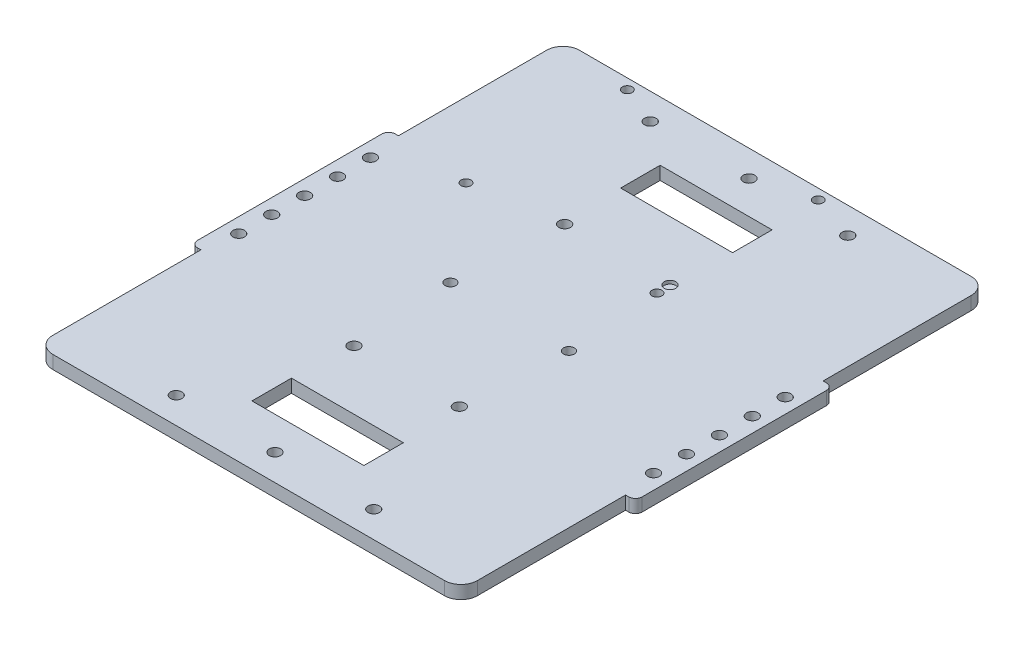
SolidWorks part; units mm, degrees
ref_plane "前视基准面" through (0, 0, 0) normal (0, 0, 1) x (1, 0, 0)
ref_plane "上视基准面" through (0, 0, 0) normal (0, 1, 0) x (1, 0, 0)
ref_plane "右视基准面" through (0, 0, 0) normal (1, 0, 0) x (0, 0, -1)
sketch "草图1" plane through (0, 0, 0) normal (0, 1, 0) x (1, 0, 0)
  line L1 (-67.5, 50) -> (67.5, 50)
  line L2 (-67.5, 50) -> (-67.5, -50)
  line L3 (-67.5, -50) -> (67.5, -50)
  line L4 (67.5, 50) -> (67.5, -50)
  line L5 (-67.5, 50) -> (67.5, -50) construction
  line L6 (-67.5, -50) -> (67.5, 50) construction
  point P0 (0, 0)
  dimension "D1" = 100
  dimension "D2" = 135
extrude "凸台-拉伸1" add sketch "草图1" along normal blind 4
sketch "草图2" plane through (0, 0, 50) normal (0, 0, 1) x (1, 0, 0)
  line L4 (-67.5, 0) -> (67.5, 0)
  line L5 (67.5, 0) -> (67.5, 4)
  line L6 (67.5, 4) -> (-67.5, 4)
  line L7 (-67.5, 4) -> (-67.5, 0)
  line L8 (-67.5, 0) -> (67.5, 0)
  line L9 (67.5, 0) -> (67.5, 4)
  line L10 (67.5, 4) -> (-67.5, 4)
  line L11 (-67.5, 4) -> (-67.5, 0)
  dimension "D1" = 0
extrude "凸台-拉伸2" add sketch "草图2" along normal blind 60
sketch "草图3" plane through (0, 4, 0) normal (0, 1, 0) x (1, 0, 0)
  line L1 (-67.5, 50) -> (-64.5, 50)
  line L2 (-67.5, 50) -> (-67.5, 0)
  line L3 (-67.5, 0) -> (-64.5, 0)
  line L4 (-64.5, 50) -> (-64.5, 0)
  line L5 (67.5, 50) -> (64.5, 50)
  line L6 (67.5, 50) -> (67.5, 0)
  line L7 (67.5, 0) -> (64.5, 0)
  line L8 (64.5, 50) -> (64.5, 0)
  line L9 (-67.5, -110) -> (-64.5, -110)
  line L10 (-67.5, -110) -> (-67.5, -60)
  line L11 (-67.5, -60) -> (-64.5, -60)
  line L12 (-64.5, -110) -> (-64.5, -60)
  line L13 (67.5, -110) -> (64.5, -110)
  line L14 (67.5, -110) -> (67.5, -60)
  line L15 (67.5, -60) -> (64.5, -60)
  line L16 (64.5, -110) -> (64.5, -60)
  dimension "D1" = 50
  dimension "D2" = 3
  dimension "D3" = 3
  dimension "D4" = 50
  dimension "D5" = 3
  dimension "D6" = 3
  dimension "D7" = 50
extrude "切除-拉伸1" cut sketch "草图3" against normal through all both and the other way through all
fillet "圆角1" radius 5 4 edges at (-64.5, 2, 110) (64.5, 2, 110) (64.5, 2, -50) (-64.5, 2, -50)
fillet "圆角2" radius 2 4 edges at (67.5, 2, 60) (67.5, 2, 0) (-67.5, 2, 60) (-67.5, 2, 0)
sketch "草图4" plane through (0, 4, 0) normal (0, 1, 0) x (1, 0, 0)
  circle A0 centre (-30, -102) radius 1.75
  circle A1 centre (0, -102) radius 1.75
  circle A2 centre (30, -102) radius 1.75
  circle A3 centre (-30, 42) radius 1.75
  circle A4 centre (0, 42) radius 1.75
  circle A5 centre (30, 42) radius 1.75
extrude "切除-拉伸2" cut sketch "草图4" against normal through all both and the other way through all
sketch "草图5" plane through (0, 4, 0) normal (0, 1, 0) x (1, 0, 0)
  line L1 (-17, -92) -> (17, -92)
  line L2 (-17, -92) -> (-17, -80)
  line L3 (-17, -80) -> (17, -80)
  line L4 (17, -92) -> (17, -80)
  line L5 (-17, 20) -> (17, 20)
  line L6 (-17, 20) -> (-17, 32)
  line L7 (-17, 32) -> (17, 32)
  line L8 (17, 20) -> (17, 32)
extrude "切除-拉伸3" cut sketch "草图5" against normal through all both and the other way through all
sketch "草图6" plane through (0, 0, 0) normal (0, -1, 0) x (1, 0, 0)
  circle A0 centre (-16, -2) radius 1.75
  circle A1 centre (16, -2) radius 1.75
  circle A2 centre (16, 62) radius 1.75
  circle A3 centre (-16, 62) radius 1.75
  dimension "D1" = 3.5
  dimension "D2" = 3.5
  dimension "D3" = 3.5
  dimension "D4" = 3.5
extrude "切除-拉伸4" cut sketch "草图6" against normal through all both and the other way through all
sketch "草图7" plane through (0, 0, 0) normal (0, -1, 0) x (1, 0, 0)
  circle A0 centre (18, 30.7) radius 1.6349
  circle A1 centre (-18, 30.7) radius 1.6349
extrude "切除-拉伸5" cut sketch "草图7" against normal through all both and the other way through all
sketch "草图8" plane through (0, 0, 0) normal (0, -1, 0) x (1, 0, 0)
  circle A0 centre (-41.8612, 2.111) radius 1.5
  circle A1 centre (-41.8612, -46.8856) radius 1.5
  circle A2 centre (16.1388, 2.111) radius 1.5
  circle A3 centre (16.1388, -46.8856) radius 1.5
  dimension "D1" = 3
extrude "切除-拉伸6" cut sketch "草图8" against normal through all both and the other way through all
sketch "草图9" plane through (0, 0, 0) normal (0, -1, 0) x (1, 0, 0)
  circle A0 centre (16, -2) radius 1.75 construction
  circle A1 centre (16, -2) radius 1.75
extrude "凸台-拉伸3" add sketch "草图9" against normal blind 3
sketch "草图10" plane through (0, 4, 0) normal (0, 1, 0) x (1, 0, 0)
  circle A0 centre (63, -10) radius 1.75
  circle A1 centre (63, -20) radius 1.75
  circle A2 centre (63, -30) radius 1.75
  circle A3 centre (63, -40) radius 1.75
  circle A4 centre (63, -50) radius 1.75
  circle A5 centre (-63, -10) radius 1.75
  circle A6 centre (-63, -20) radius 1.75
  circle A7 centre (-63, -30) radius 1.75
  circle A8 centre (-63, -40) radius 1.75
  circle A9 centre (-63, -50) radius 1.75
extrude "切除-拉伸7" cut sketch "草图10" against normal through all both and the other way through all
